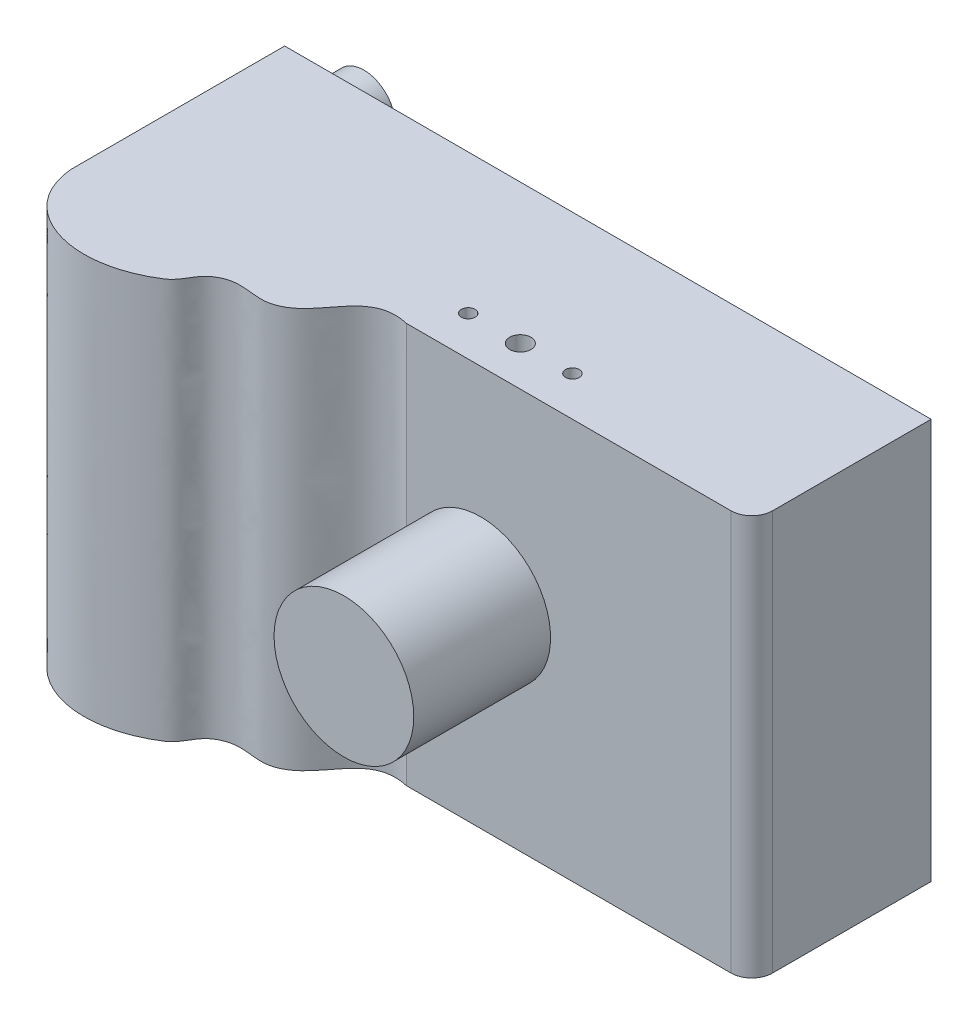
SolidWorks part; units mm, degrees
material "1060 Alloy"
ref_plane "Front Plane" through (0, 0, 0) normal (0, 0, 1) x (1, 0, 0)
ref_plane "Top Plane" through (0, 0, 0) normal (0, 1, 0) x (1, 0, 0)
ref_plane "Right Plane" through (0, 0, 0) normal (1, 0, 0) x (0, 0, -1)
sketch "Sketch3" plane through (0, 0, 0) normal (0, 1, 0) x (1, 0, 0)
  line L0 (-77.5, 33.7134) -> (77.5, 33.7134)
  line L1 (77.5, 33.7134) -> (77.5, -4.2866)
  line L2 (72.5, -9.2866) -> (-5.3428, -9.2866)
  line L3 (-77.5, 33.7134) -> (-77.5, -17.5926)
  arc A0 (72.5, -9.2866) -> (77.5, -4.2866) centre (72.5, -4.2866) ccw
  spline S0 degree 3 poles (-77.5, -17.5926) (-76.5316, -27.8124) (-63.1834, -36.2255) (-48.3099, -32.1916) (-41.5482, -27.7916) (-39.9233, -23.2529) (-33.5166, -20.4028) (-27.6368, -22.4573) (-17.0165, -17.9926) (-15.4515, -6.9316) (-5.3428, -9.2866) knots 0 0 0 0 0.287416 0.468368 0.496457 0.560076 0.621962 0.714917 0.759402 1 1 1 1
  dimension "D1" = 5
  dimension "D2" = 155
  dimension "D3" = 43
  dimension "D4" = 67.25
extrude "Boss-Extrude2" add sketch "Sketch3" along normal blind 96
hole_wizard "1/4-20 Tapped Hole1" positions "Sketch5" profile "Sketch7" tap size "1/4-20" standard "ANSI Inch"
sketch "Sketch5" plane through (-77.5, 0, 0) normal (-1, 0, 0) x (0, 0, 1)
  line L0 (-33.7134, 96) -> (-33.7134, 0) construction
  line L1 (-33.7134, 0) -> (17.5926, 0) construction
  point P0 (-0.2134, 47.5)
  dimension "D1" = 33.5
  dimension "D2" = 47.5
sketch "Sketch7" plane through (-77.5, 47.5, -0.2134) normal (0, 1, 0) x (0, 0, 1)
  line L0 (0, 0) -> (0, 13.3438)
  line L1 (0, 13.3438) -> (2.5527, 11.81)
  line L2 (2.5527, 11.81) -> (2.5527, 0)
  line L5 (2.5527, 0) -> (0, 0)
  line L10 (0, 13.3438) -> (-2.5527, 11.81) construction
  line L11 (0, -6.35) -> (0, 107.95) construction
  dimension "Tap Drill Dia." = 5.1054
  dimension "Tap Drill Depth" = 11.81
  dimension "Drill Angle" = 118
cosmetic thread "Hole Thread1" parameters "D1"=8, "D2"=6.35
hole_wizard "M4x0.7 Tapped Hole1" positions "Sketch8" profile "Sketch9" tap size "M4x0.7" standard "ANSI Metric"
sketch "Sketch8" plane through (-77.5, 0, 0) normal (-1, 0, 0) x (0, 0, 1)
  point P0 (-0.2134, 85)
  point P2 (-0.2134, 10)
  dimension "D1" = 37.5
  dimension "D2" = 37.5
sketch "Sketch9" plane through (-77.5, 85, -0.2134) normal (0, 1, 0) x (0, 0, 1)
  line L0 (0, 0) -> (0, 8.9914)
  line L1 (0, 8.9914) -> (1.65, 8)
  line L2 (1.65, 8) -> (1.65, 0)
  line L5 (1.65, 0) -> (0, 0)
  line L10 (0, 8.9914) -> (-1.65, 8) construction
  line L11 (0, -6.35) -> (0, 107.95) construction
  dimension "Tap Drill Dia." = 3.3
  dimension "Tap Drill Depth" = 8
  dimension "Drill Angle" = 118
cosmetic thread "Hole Thread2" parameters "D1"=8, "D2"=4
cosmetic thread "Hole Thread3" parameters "D1"=8, "D2"=4
hole_wizard "1/4-20 Tapped Hole2" positions "Sketch10" profile "Sketch11" tap size "1/4-20" standard "ANSI Inch"
sketch "Sketch10" plane through (0, 0, 0) normal (0, -1, 0) x (-1, 0, 0)
  line L0 (77.5, 33.7134) -> (77.5, -17.5926) construction
  line L1 (-77.5, 33.7134) -> (77.5, 33.7134) construction
  point P0 (-12.5, 10.2134)
  dimension "D1" = 90
  dimension "D2" = 23.5
sketch "Sketch11" plane through (12.5, 0, -10.2134) normal (1, 0, 0) x (0, 0, -1)
  line L0 (0, 0) -> (0, 9.5338)
  line L1 (0, 9.5338) -> (2.5527, 8)
  line L2 (2.5527, 8) -> (2.5527, 0)
  line L5 (2.5527, 0) -> (0, 0)
  line L10 (0, 9.5338) -> (-2.5527, 8) construction
  line L11 (0, -6.35) -> (0, 107.95) construction
  dimension "Tap Drill Dia." = 5.1054
  dimension "Tap Drill Depth" = 8
  dimension "Drill Angle" = 118
cosmetic thread "Hole Thread4" parameters "D1"=8, "D2"=6.35
hole_wizard "M4x0.7 Tapped Hole2" positions "Sketch12" profile "Sketch13" tap size "M4x0.7" standard "ANSI Metric"
sketch "Sketch12" plane through (0, 0, 0) normal (0, -1, 0) x (-1, 0, 0)
  line L0 (-77.5, 33.7134) -> (77.5, 33.7134) construction
  point P0 (0, 0.2134)
  point P2 (-25, 0.2134)
  dimension "D1" = 33.5
  dimension "D2" = 12.5
  dimension "D3" = 12.5
sketch "Sketch13" plane through (0, 0, -0.2134) normal (1, 0, 0) x (0, 0, -1)
  line L0 (0, 0) -> (0, 8.9914)
  line L1 (0, 8.9914) -> (1.65, 8)
  line L2 (1.65, 8) -> (1.65, 0)
  line L5 (1.65, 0) -> (0, 0)
  line L10 (0, 8.9914) -> (-1.65, 8) construction
  line L11 (0, -6.35) -> (0, 107.95) construction
  dimension "Tap Drill Dia." = 3.3
  dimension "Tap Drill Depth" = 8
  dimension "Drill Angle" = 118
cosmetic thread "Hole Thread5" parameters "D1"=8, "D2"=4
cosmetic thread "Hole Thread6" parameters "D1"=8, "D2"=4
hole_wizard "1/4-20 Tapped Hole3" positions "Sketch14" profile "Sketch15" tap size "1/4-20" standard "ANSI Inch"
sketch "Sketch14" plane through (0, 96, 0) normal (0, 1, 0) x (1, 0, 0)
  line L0 (77.5, 33.7134) -> (-77.5, 33.7134) construction
  line L1 (-77.5, 33.7134) -> (-77.5, -17.5926) construction
  point P0 (12.5, 0.2134)
  dimension "D1" = 33.5
  dimension "D2" = 90
sketch "Sketch15" plane through (12.5, 96, -0.2134) normal (1, 0, 0) x (0, 0, 1)
  line L0 (0, 0) -> (0, 9.5338)
  line L1 (0, 9.5338) -> (2.5527, 8)
  line L2 (2.5527, 8) -> (2.5527, 0)
  line L5 (2.5527, 0) -> (0, 0)
  line L10 (0, 9.5338) -> (-2.5527, 8) construction
  line L11 (0, -6.35) -> (0, 107.95) construction
  dimension "Tap Drill Dia." = 5.1054
  dimension "Tap Drill Depth" = 8
  dimension "Drill Angle" = 118
cosmetic thread "Hole Thread7" parameters "D1"=8, "D2"=6.35
hole_wizard "M4x0.7 Tapped Hole3" positions "Sketch16" profile "Sketch17" tap size "M4x0.7" standard "ANSI Metric"
sketch "Sketch16" plane through (0, 96, 0) normal (0, 1, 0) x (1, 0, 0)
  point P0 (25, 0.2134)
  point P4 (0, 0.2134)
  dimension "D1" = 12.5
  dimension "D2" = 12.5
sketch "Sketch17" plane through (25, 96, -0.2134) normal (1, 0, 0) x (0, 0, 1)
  line L0 (0, 0) -> (0, 8.9914)
  line L1 (0, 8.9914) -> (1.65, 8)
  line L2 (1.65, 8) -> (1.65, 0)
  line L5 (1.65, 0) -> (0, 0)
  line L10 (0, 8.9914) -> (-1.65, 8) construction
  line L11 (0, -6.35) -> (0, 107.95) construction
  dimension "Tap Drill Dia." = 3.3
  dimension "Tap Drill Depth" = 8
  dimension "Drill Angle" = 118
cosmetic thread "Hole Thread8" parameters "D1"=8, "D2"=4
cosmetic thread "Hole Thread9" parameters "D1"=8, "D2"=4
sketch "Sketch18" plane through (0, 0, 9.2866) normal (0, 0, 1) x (1, 0, 0)
  line L0 (-77.5, 96) -> (-77.5, 0) construction
  line L1 (-5.3428, 0) -> (72.5, 0) construction
  circle A0 centre (12.5, 48) radius 15
  dimension "D2" = 30
  dimension "D1" = 90
  dimension "D3" = 48
extrude "Boss-Extrude3" add sketch "Sketch18" along normal blind 7
sketch "Sketch19" plane through (0, 0, 9.2866) normal (0, 0, 1) x (1, 0, 0)
  circle A0 centre (12.5, 48) radius 16.75
  dimension "D1" = 33.5
extrude "Boss-Extrude4" add sketch "Sketch19" along normal blind 32.8
sketch "Sketch21" plane through (0, 0, -33.7134) normal (0, 0, -1) x (-1, 0, 0)
  line L0 (-77.5, 0) -> (77.5, 0) construction
  line L1 (77.5, 96) -> (77.5, 0) construction
  circle A0 centre (66.5, 85) radius 7.5
  dimension "D2" = 15
  dimension "D1" = 85
  dimension "D3" = 11
extrude "Boss-Extrude5" add sketch "Sketch21" along normal blind 8
